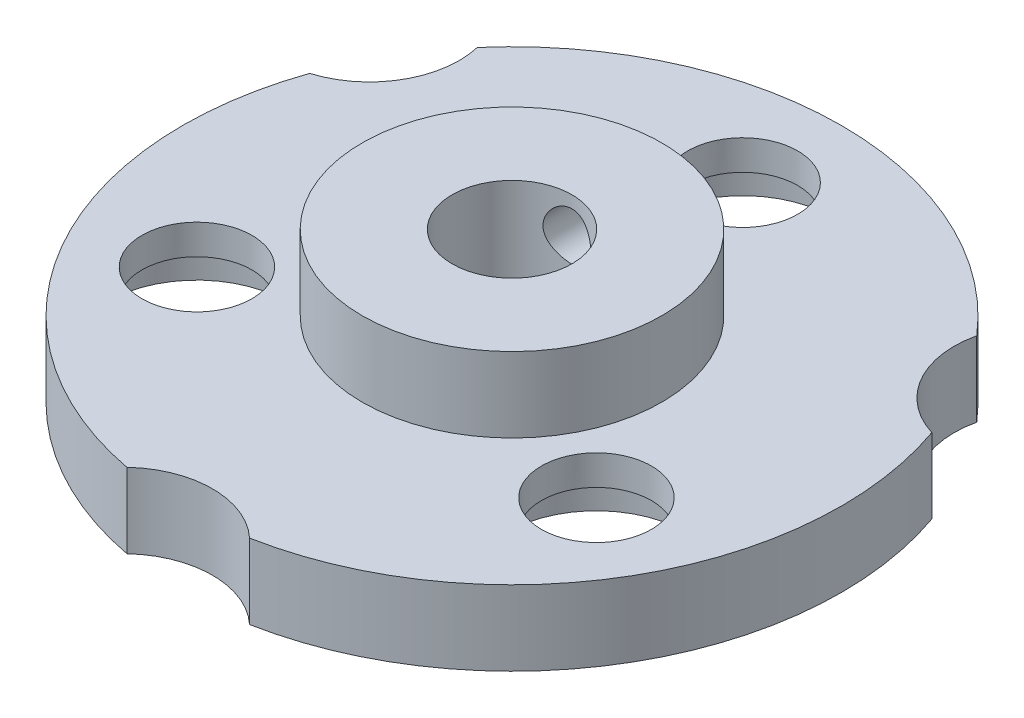
SolidWorks part; units mm, degrees
ref_plane "Plano frontal" through (0, 0, 0) normal (0, 0, 1) x (1, 0, 0)
ref_plane "Plano superior" through (0, 0, 0) normal (0, 1, 0) x (1, 0, 0)
ref_plane "Plano direito" through (0, 0, 0) normal (1, 0, 0) x (0, 0, -1)
sketch "Esboço1" plane through (0, 0, 0) normal (0, 1, 0) x (1, 0, 0)
  circle A0 centre (0, 0) radius 11
  dimension "D1" = 22
extrude "Ressalto-extrusão1" add sketch "Esboço1" along normal blind 2.5
sketch "Esboço3" plane through (0, 2.5, 0) normal (0, 1, 0) x (1, 0, 0)
  circle A1 centre (0, 7.7) radius 1.8355
  circle A2 centre (6.6684, -3.85) radius 1.8355
  circle A3 centre (-6.6684, -3.85) radius 1.8355
  dimension "D1" = 7.7
  dimension "D2" = 7.7
extrude "Corte-extrusão1" cut sketch "Esboço3" against normal blind 2.5
sketch "Esboço18" plane through (0, 2.5, 0) normal (0, 1, 0) x (1, 0, 0)
  circle A0 centre (0, 0) radius 5
  dimension "D1" = 10
extrude "Ressalto-extrusão5" add sketch "Esboço18" along normal blind 2.5
sketch "Esboço20" plane through (0, 5, 0) normal (0, 1, 0) x (1, 0, 0)
  circle A0 centre (0, 0) radius 2
  dimension "D1" = 4
extrude "Corte-extrusão5" cut sketch "Esboço20" against normal blind 5.5
hole_wizard "Broca de rosquear para tarraxa de M2x0.42" positions "3DSketch3" profile "Esboço21" hole size "M2x0.4" standard "Ansi Metric"
sketch3d "3DSketch3"
  point P0 (0.0026, 3.793, -5)
sketch "Esboço21" plane through (0.0026, 3.793, -5) normal (0, 1, 0) x (-1, 0, -0.0005)
  line L0 (0, 0) -> (0, 3)
  line L1 (0, 3) -> (0.8, 3)
  line L2 (0.8, 3) -> (0.8, 0)
  line L5 (0.8, 0) -> (0, 0)
  line L11 (0, -6.35) -> (0, 107.95) construction
  dimension "Thru Hole Dia." = 1.6
  dimension "Thru Hole Depth" = 3
sketch "Esboço22" plane through (0, 2.5, 0) normal (0, 1, 0) x (1, 0, 0)
  circle A1 centre (-11.2583, 6.5) radius 3
  circle A2 centre (0, -13) radius 3
  circle A3 centre (11.2583, 6.5) radius 3
  dimension "D1" = 6
extrude "Corte-extrusão6" cut sketch "Esboço22" against normal blind 5.5
sketch "Esboço23" plane through (0, 0, 0) normal (0, -1, 0) x (-1, 0, 0)
  circle A0 centre (-6.6684, -3.85) radius 3
  circle A1 centre (6.6684, -3.85) radius 3
  circle A2 centre (0, 7.7) radius 3
  dimension "D1" = 6
extrude "Corte-extrusão7" cut sketch "Esboço23" against normal blind 1.5
